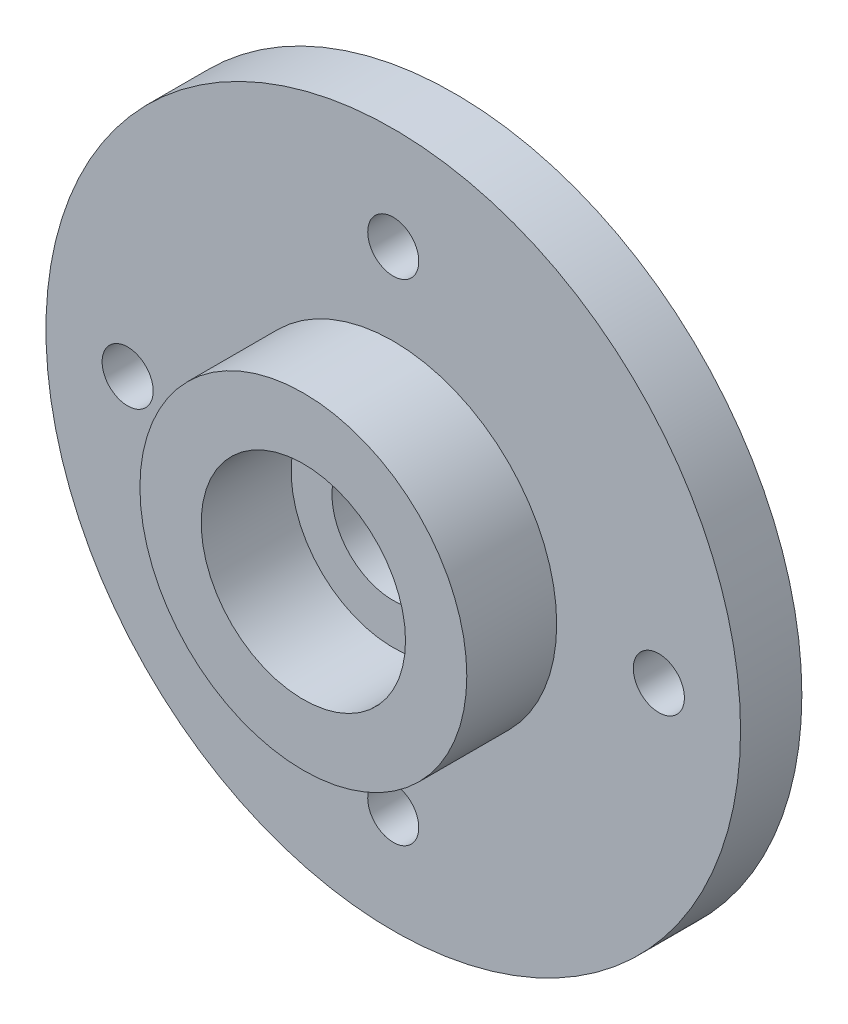
SolidWorks part; units mm, degrees
ref_plane "Front Plane" through (0, 0, 0) normal (0, 0, 1) x (1, 0, 0)
ref_plane "Top Plane" through (0, 0, 0) normal (0, 1, 0) x (1, 0, 0)
ref_plane "Right Plane" through (0, 0, 0) normal (1, 0, 0) x (0, 0, -1)
sketch "Sketch1" plane through (0, 0, 0) normal (0, 0, 1) x (1, 0, 0)
  circle A0 centre (0, 0) radius 8.5
extrude "Boss-Extrude1" add sketch "Sketch1" along normal blind 1.5
sketch "Sketch2" plane through (0, 0, 0) normal (0, 0, 1) x (1, 0, 0)
  circle A0 centre (0, 0) radius 4
  circle A1 centre (0, 0) radius 2.5
extrude "Boss-Extrude2" add sketch "Sketch2" along normal blind 3.7
sketch "Sketch3" plane through (0, 0, 0) normal (0, 0, 1) x (1, 0, 0)
  circle A0 centre (0, 0) radius 1.5
extrude "Cut-Extrude1" cut sketch "Sketch3" along normal blind 2
sketch "Sketch4" plane through (0, 0, 0) normal (0, 0, 1) x (1, 0, 0)
  line L0 (0, 0) -> (13, 0) construction
  line L1 (0, 0) -> (-13, 0) construction
  circle A0 centre (6.5, 0) radius 0.625
  dimension "D3" = 6.5
extrude "Cut-Extrude2" cut sketch "Sketch4" along normal blind 2
pattern_circular "CirPattern1" count 2 over 360 about axis through (0, 0, 0) along (0, 0, 1) of "Cut-Extrude2"
sketch "Sketch5" plane through (0, 0, 0) normal (0, 0, -1) x (-1, 0, 0)
  circle A0 centre (0, 6) radius 0.625
  circle A1 centre (0, -6) radius 0.625
  circle A2 centre (0, 0) radius 1.5 construction
  dimension "D1" = 6
  dimension "D2" = 6
  dimension "D3" = 1.25
  dimension "D4" = 1.25
extrude "Cut-Extrude3" cut sketch "Sketch5" against normal blind 1.5
sketch "Sketch6" plane through (0, 0, 0) normal (0, 0, -1) x (-1, 0, 0)
  circle A0 centre (0, 0) radius 3.5
  circle A1 centre (0, 0) radius 3
extrude "Boss-Extrude3" add sketch "Sketch6" along normal blind 1
